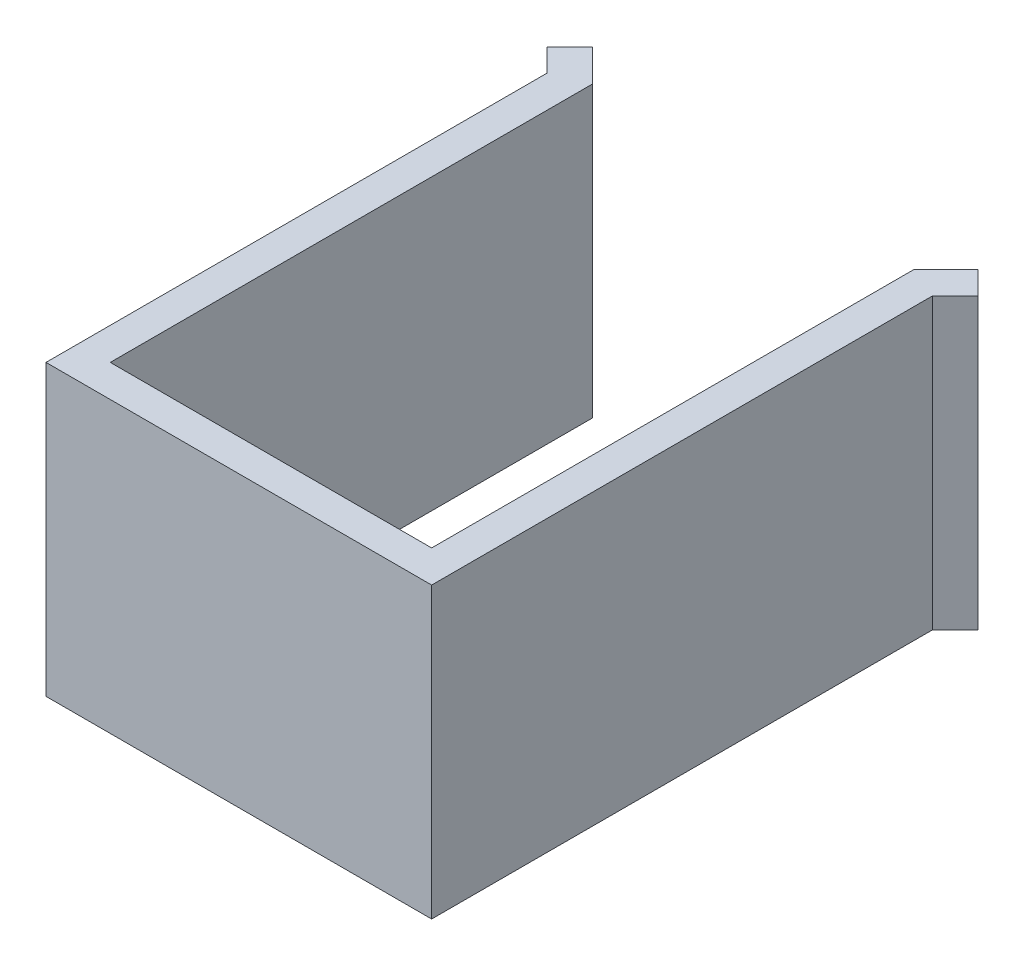
SolidWorks part; units mm, degrees
ref_plane "Přední rovina" through (0, 0, 0) normal (0, 0, 1) x (1, 0, 0)
ref_plane "Vrchní rovina" through (0, 0, 0) normal (0, 1, 0) x (1, 0, 0)
ref_plane "Pravá rovina" through (0, 0, 0) normal (1, 0, 0) x (0, 0, -1)
sketch "Skica78" plane through (0, 0, 0) normal (0, 1, 0) x (1, 0, 0)
  line L0 (50, 0) -> (-50, 0)
  line L1 (-50, 0) -> (-50, 150)
  line L2 (-50, 150) -> (-60, 160)
  line L3 (0, 0) -> (0, 242.2592) construction
  line L4 (50, 150) -> (60, 160)
  line L5 (50, 0) -> (50, 150)
  dimension "D1" = 150
  dimension "D2" = 100
  dimension "D3" = 45
  dimension "D4" = 160
extrude "Vysunout tenkostěnný1" add sketch "Skica78" along normal blind 90 thin thin type one direction wall 10
